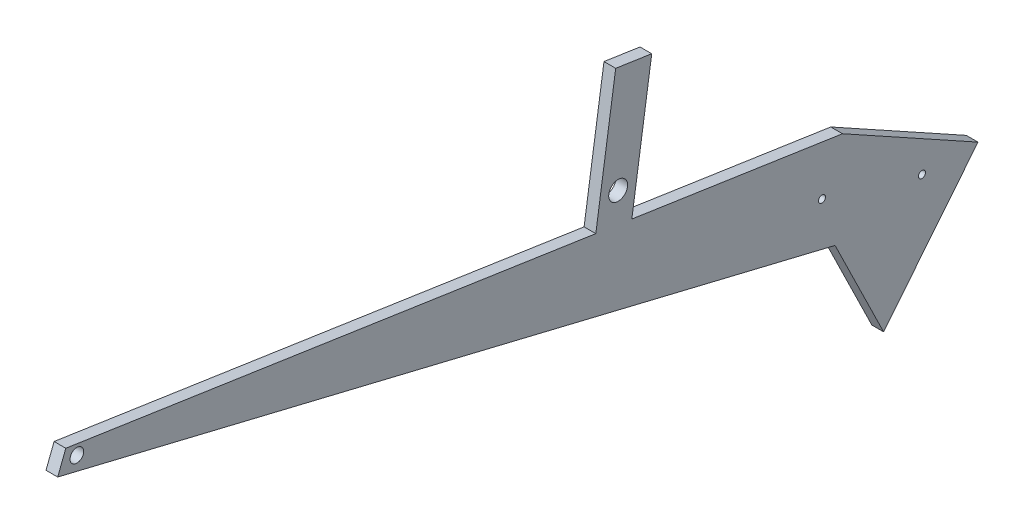
SolidWorks part; units mm, degrees
ref_plane "前视基准面" through (0, 0, 0) normal (0, 0, 1) x (1, 0, 0)
ref_plane "上视基准面" through (0, 0, 0) normal (0, 1, 0) x (1, 0, 0)
ref_plane "右视基准面" through (0, 0, 0) normal (1, 0, 0) x (0, 0, -1)
other "Configuration Table"
sketch "草图1" plane through (0, 0, 0) normal (1, 0, 0) x (0, 0, -1)
  line L0 (-129.1109, 27.705) -> (3.4977, 7.9058)
  line L1 (3.4977, 7.9058) -> (26.6352, -4.9016)
  line L2 (26.6352, -4.9016) -> (10.5195, -24.901)
  line L3 (10.5195, -24.901) -> (2.2315, -7.9796)
  line L4 (2.2315, -7.9796) -> (-130.4922, 24.1365)
  line L5 (-130.4922, 24.1365) -> (-129.1109, 27.705)
  circle A0 centre (0, 0) radius 0.6
  circle A1 centre (17.0692, -4.9016) radius 0.6
  circle A2 centre (-127.2225, 25.7178) radius 1.1621
  dimension "D1" = 1.2
  dimension "D5" = 1.2
extrude "凸台-拉伸1" add sketch "草图1" along normal blind 2
sketch "草图2" plane through (0, 8.2442, -1.2309) normal (0, 0.989, -0.1477) x (1, 0, 0)
  line L0 (0, -131.7866) -> (0, 2.2919) construction
  line L1 (0, -34.0707) -> (2, -34.0707)
  line L2 (0, -34.0707) -> (0, -40.2927)
  line L3 (0, -40.2927) -> (2, -40.2927)
  line L4 (2, -34.0707) -> (2, -40.2927)
  line L5 (2, -131.7866) -> (2, 2.2919) construction
extrude "凸台-拉伸2" add sketch "草图2" along normal through all contours L3 L4 L1 L2
sketch "草图3" plane through (2, 0, 0) normal (1, 0, 0) x (0, 0, -1)
  line L0 (-32.147, 36.4815) -> (-34.8048, 18.68)
  line L1 (-29.0701, 36.0221) -> (-35.2238, 36.9409) construction
  line L2 (-32.4663, 13.2754) -> (3.4977, 7.9058) construction
  circle A0 centre (-34.8048, 18.68) radius 1.6145
  dimension "D1" = 5
extrude "切除-拉伸1" cut sketch "草图3" against normal through all contours A0
